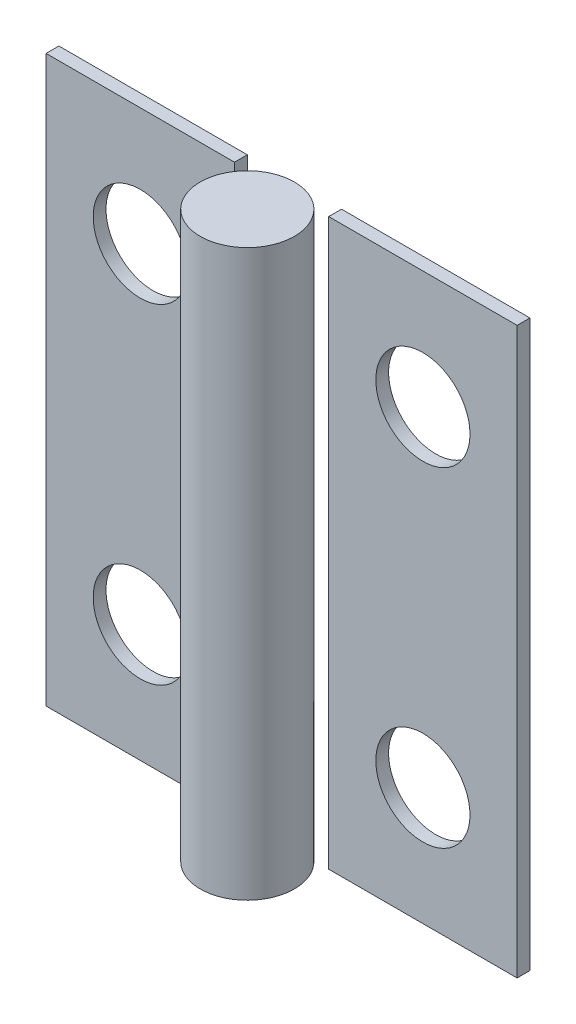
SolidWorks part; units mm, degrees
ref_plane "Front Plane" through (0, 0, 0) normal (0, 0, 1) x (1, 0, 0)
ref_plane "Top Plane" through (0, 0, 0) normal (0, 1, 0) x (1, 0, 0)
ref_plane "Right Plane" through (0, 0, 0) normal (1, 0, 0) x (0, 0, -1)
sketch "Sketch1" plane through (0, 0, 0) normal (0, 0, 1) x (1, 0, 0)
  line L0 (-4.7625, 19.05) -> (-4.7625, 0) construction
  line L1 (-7.9375, 0) -> (-1.5875, 0)
  line L2 (-7.9375, 0) -> (-7.9375, 19.05)
  line L3 (-7.9375, 19.05) -> (-1.5875, 19.05)
  line L4 (-1.5875, 0) -> (-1.5875, 19.05)
  line L5 (-1.5875, 19.05) -> (1.5875, 19.05) construction
  line L6 (-1.5875, 19.05) -> (-1.5875, 0) construction
  line L7 (-1.5875, 0) -> (1.5875, 0) construction
  line L8 (1.5875, 19.05) -> (1.5875, 0) construction
  line L9 (1.5875, 19.05) -> (7.9375, 19.05)
  line L10 (1.5875, 19.05) -> (1.5875, 0)
  line L11 (1.5875, 0) -> (7.9375, 0)
  line L12 (7.9375, 19.05) -> (7.9375, 0)
  line L13 (4.7625, 0) -> (4.7625, 19.05) construction
  line L14 (4.7625, 15.0813) -> (4.7625, 3.9688) construction
  circle A0 centre (-4.7625, 15.0813) radius 1.5875
  circle A1 centre (-4.7625, 3.9688) radius 1.5875
  circle A2 centre (4.7625, 3.9688) radius 1.5875
  circle A3 centre (4.7625, 15.0813) radius 1.5875
  point P8 (0, 0)
  point P24 (4.7625, 9.525)
  dimension "D6" = 3.175
  dimension "D1" = 19.05
  dimension "D2" = 6.35
  dimension "D3" = 3.175
  dimension "D4" = 6.35
  dimension "D5" = 19.05
  dimension "D7" = 11.1125
extrude "Boss-Extrude1" add sketch "Sketch1" along normal blind 0.4318
sketch "Sketch2" plane through (0, 0, 0) normal (0, 1, 0) x (1, 0, 0)
  line L0 (-1.5875, 0) -> (1.5875, 0) construction
  circle A0 centre (0, -1.5875) radius 1.5875
  dimension "D1" = 3.175
extrude "Boss-Extrude2" add sketch "Sketch2" along normal blind 19.05 separate body
